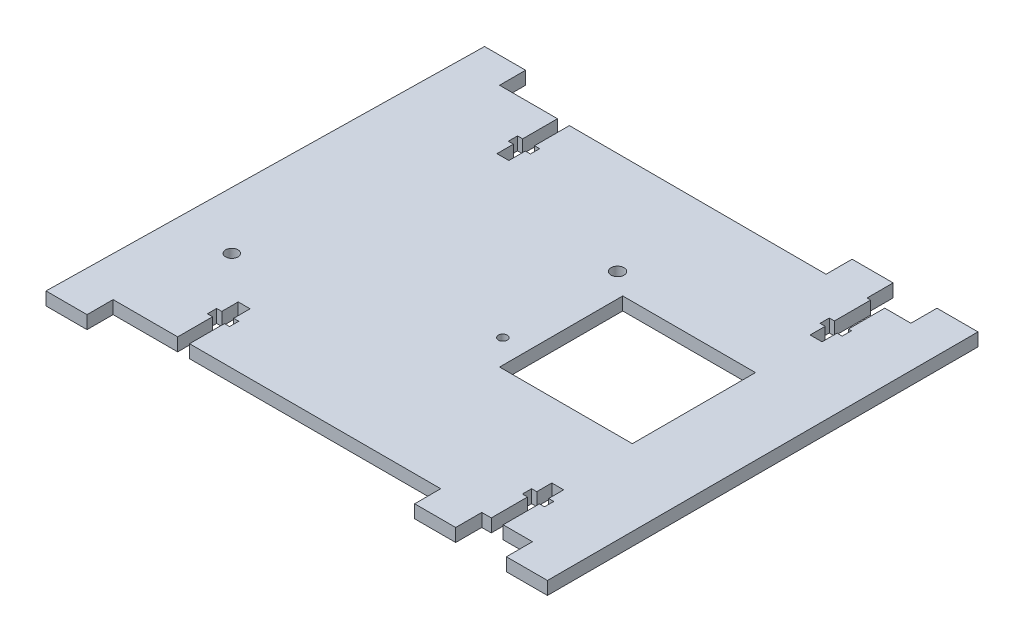
SolidWorks part; units mm, degrees
ref_plane "Front Plane" through (0, 0, 0) normal (0, 0, 1) x (1, 0, 0)
ref_plane "Top Plane" through (0, 0, 0) normal (0, 1, 0) x (1, 0, 0)
ref_plane "Right Plane" through (0, 0, 0) normal (1, 0, 0) x (0, 0, -1)
sketch "Sketch1" plane through (0, 0, 0) normal (0, 1, 0) x (1, 0, 0)
  line L0 (-67.1586, 70.4843) -> (-67.1586, 74.4928)
  line L1 (-81.2791, 85.2343) -> (-81.2791, 91.5843)
  line L2 (-91.2791, 91.5843) -> (-81.2791, 91.5843)
  line L3 (6.6867, -7.0657) -> (6.6867, -13.4171)
  line L4 (12.1457, 70.3826) -> (12.1457, 74.0459)
  line L5 (-64.2586, 85.2343) -> (-1.6286, 85.1326)
  line L6 (-67.1586, 85.2343) -> (-67.1586, 76.7428)
  line L7 (-67.1586, 70.4843) -> (-64.2586, 70.4843)
  line L8 (-64.2586, 85.2343) -> (-64.2586, 76.7428)
  line L9 (-68.4086, 76.7428) -> (-67.1586, 76.7428)
  line L10 (-68.4086, 76.7428) -> (-68.4086, 74.4928)
  line L11 (-68.4086, 74.4928) -> (-67.1586, 74.4928)
  line L12 (-63.0086, 76.7428) -> (-63.0086, 74.4928)
  line L13 (9.2457, 70.3826) -> (9.2457, 74.0459)
  line L14 (-91.2791, 91.5843) -> (-93.1321, -13.4157)
  line L15 (-81.2791, 85.2343) -> (-67.1586, 85.2343)
  line L16 (-1.6286, 91.4826) -> (-1.6286, 85.1326)
  line L17 (-64.2586, 70.4843) -> (-64.2586, 74.4928)
  line L18 (-64.2586, 74.4928) -> (-63.0086, 74.4928)
  line L19 (-64.2586, 76.7428) -> (-63.0086, 76.7428)
  line L20 (-1.6286, 91.4826) -> (8.3714, 91.4826)
  line L22 (9.2457, 85.1326) -> (9.2457, 76.2959)
  line L23 (9.2457, 70.3826) -> (12.1457, 70.3826)
  line L24 (-3.3119, -7.0657) -> (-3.3133, -13.4171)
  line L25 (7.9957, 76.2959) -> (9.2457, 76.2959)
  line L26 (7.9957, 76.2959) -> (7.9957, 74.0459)
  line L27 (7.9957, 74.0459) -> (9.2457, 74.0459)
  line L28 (12.1457, 74.0459) -> (13.3957, 74.0459)
  line L29 (8.3714, 91.4826) -> (8.3714, 85.1326)
  line L30 (8.3714, 85.1326) -> (9.2457, 85.1326)
  line L31 (13.1517, 1.771) -> (11.9017, 1.771)
  line L32 (13.3957, 74.0459) -> (13.3957, 76.2959)
  line L33 (13.3957, 76.2959) -> (12.6681, 76.2959)
  line L34 (12.6681, 76.2959) -> (12.6681, 85.1326)
  line L35 (11.9017, 1.771) -> (11.9017, -7.0657)
  line L36 (-83.1321, -7.0657) -> (-67.4026, -7.0657)
  line L37 (-1.6286, 86.7321) -> (-1.6286, 94.0829) construction
  line L38 (19.043, -10.0334) -> (19.043, -6.8584) construction
  line L39 (11.9017, 4.021) -> (13.1517, 4.021)
  line L40 (11.9017, 7.6843) -> (11.9017, 4.021)
  line L41 (19.043, -7.0657) -> (19.043, -13.4171)
  line L42 (19.043, -13.4171) -> (29.043, -13.4171)
  line L43 (29.043, 91.4826) -> (29.043, -13.4171)
  line L44 (13.1517, 1.771) -> (13.1517, 4.021)
  line L45 (7.7517, 4.021) -> (9.0017, 4.021)
  line L46 (7.7517, 1.771) -> (7.7517, 4.021)
  line L47 (7.7517, 1.771) -> (9.0017, 1.771)
  line L48 (19.043, 91.4826) -> (19.043, 85.1325)
  line L49 (9.0017, 7.6843) -> (11.9017, 7.6843)
  line L50 (9.0017, -7.0657) -> (9.0017, 1.771)
  line L51 (12.6681, 85.1326) -> (19.043, 85.1325)
  line L52 (-3.3133, -13.4171) -> (6.6867, -13.4171)
  line L53 (-64.5026, 1.4258) -> (-63.2526, 1.4258)
  line L54 (-64.5026, 3.6758) -> (-63.2526, 3.6758)
  line L55 (-64.5026, 7.6843) -> (-64.5026, 3.6758)
  line L56 (-3.3119, -7.0657) -> (-64.5026, -7.0657)
  line L57 (-83.1321, -13.4157) -> (-83.1321, -7.0657)
  line L58 (9.0017, 7.6843) -> (9.0017, 4.021)
  line L59 (-63.2526, 1.4258) -> (-63.2526, 3.6758)
  line L60 (-68.6526, 3.6758) -> (-67.4026, 3.6758)
  line L61 (-68.6526, 1.4258) -> (-68.6526, 3.6758)
  line L62 (-68.6526, 1.4258) -> (-67.4026, 1.4258)
  line L63 (-64.5026, -7.0657) -> (-64.5026, 1.4258)
  line L64 (-67.4026, 7.6843) -> (-64.5026, 7.6843)
  line L65 (-67.4026, -7.0657) -> (-67.4026, 1.4258)
  line L66 (11.9017, -7.0657) -> (19.043, -7.0657)
  line L67 (-93.1321, -13.4157) -> (-83.1321, -13.4157)
  line L68 (-67.4026, 7.6843) -> (-67.4026, 3.6758)
  line L69 (-21.8187, 55.7843) -> (10.5266, 55.7843)
  line L70 (-21.8187, 55.7843) -> (-21.8187, 25.7843)
  line L71 (-21.8187, 25.7843) -> (10.5266, 25.7843)
  line L72 (10.5266, 55.7843) -> (10.5266, 25.7843)
  line L73 (29.043, 91.4826) -> (29.043, -13.4171)
  line L77 (-91.2791, 93.0444) -> (-91.2791, -11.9556) construction
  line L78 (6.6867, -7.0657) -> (9.0017, -7.0657)
  line L79 (19.043, 91.4826) -> (29.043, 91.4826)
  circle A7 centre (-78.423, 17.1475) radius 1.5071
  circle A8 centre (-27.6231, 32.3875) radius 1.0795
  circle A9 centre (-27.6231, 60.3275) radius 1.5835
  dimension "D26" = 8.8367
  dimension "D1" = 1.25
  dimension "D2" = 2.9
  dimension "D3" = 1.25
  dimension "D4" = 2.25
  dimension "D5" = 14.75
  dimension "D6" = 1.25
  dimension "D7" = 1.25
  dimension "D8" = 2.25
  dimension "D9" = 14.75
  dimension "D10" = 10
  dimension "D11" = 10
  dimension "D12" = 10
  dimension "D13" = 10
  dimension "D14" = 10
  dimension "D15" = 6.3514
  dimension "D16" = 105
  dimension "D17" = 6.35
  dimension "D18" = 30
  dimension "D19" = 10
  dimension "D20" = 2.315
  dimension "D21" = 6.35
  dimension "D22" = 6.35
  dimension "D23" = 6.3514
  dimension "D24" = 8.8367
  dimension "D25" = 1.25
  dimension "D27" = 2.25
  dimension "D28" = 6.3501
  dimension "D29" = 6.3749
extrude "Extrude1" add sketch "Sketch1" along normal blind 3.175
